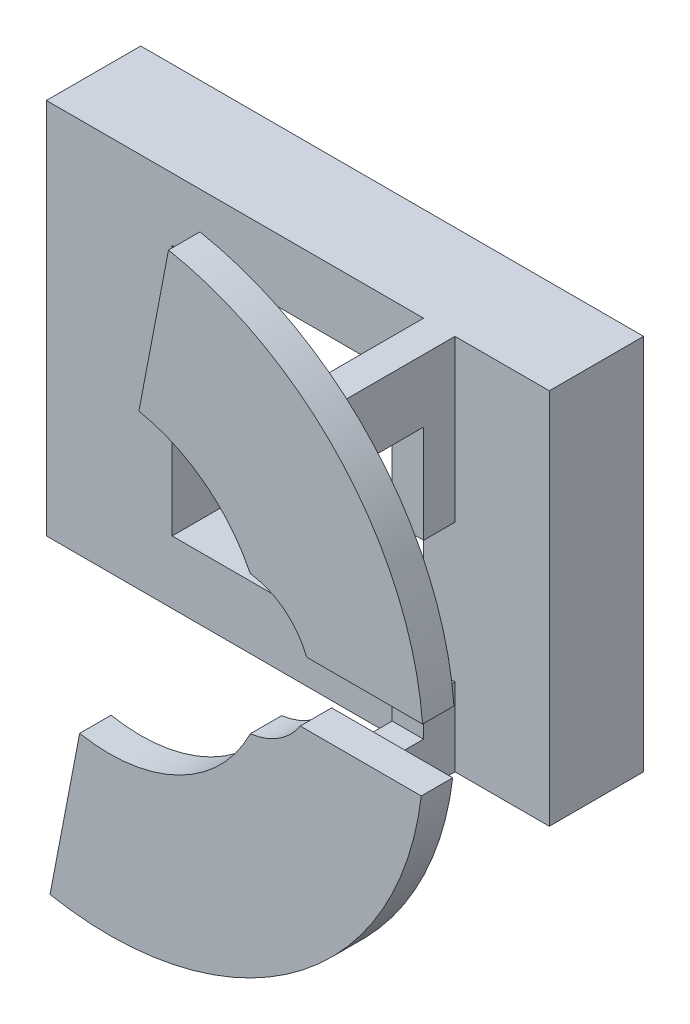
SolidWorks part; units mm, degrees
ref_plane "Front Plane" through (0, 0, 0) normal (1, 0, 0) x (0, 1, 0)
ref_plane "Top Plane" through (0, 0, 0) normal (0, 0, 1) x (0, 1, 0)
ref_plane "Right Plane" through (0, 0, 0) normal (0, 1, 0) x (-1, 0, 0)
sketch "Sketch2" plane through (0, 0, 0) normal (0, 0, 1) x (0, 1, 0)
  line L1 (-20, 20) -> (20, 20)
  line L2 (-20, 20) -> (-20, -20)
  line L3 (-20, -20) -> (20, -20)
  line L4 (20, 20) -> (20, -20)
  line L5 (-20, 20) -> (20, -20) construction
  line L6 (-20, -20) -> (20, 20) construction
  line L11 (-30, -40) -> (30, -40)
  line L12 (-30, -40) -> (-30, 40)
  line L13 (-30, 40) -> (30, 40)
  line L14 (30, -40) -> (30, 40)
  line L15 (-30, -40) -> (30, 40) construction
  line L16 (-30, 40) -> (30, -40) construction
  point P0 (0, 0)
  point P6 (0, 0)
  dimension "D1" = 40
  dimension "D2" = 80
  dimension "D3" = 60
extrude "Boss-Extrude1" add sketch "Sketch2" along normal blind 15
sketch "Sketch6" plane through (0, 0, 15) normal (0, 0, 1) x (1, 0, 0)
  line L0 (40, 30) -> (-40, 30) construction
  line L1 (25, 30) -> (20, 30)
  line L2 (25, 30) -> (25, 4.4)
  line L3 (25, 4.4) -> (20, 4.4)
  line L4 (20, 30) -> (20, 4.4)
  line L5 (20, -20) -> (20, 20) construction
  line L6 (-40, -30) -> (40, -30) construction
  line L7 (25, -30) -> (20, -30)
  line L8 (25, -30) -> (25, -17.6)
  line L9 (25, -17.6) -> (20, -17.6)
  line L10 (20, -30) -> (20, -17.6)
  dimension "D1" = 5
  dimension "D2" = 25.6
  dimension "D3" = 12.4
extrude "Boss-Extrude4" add sketch "Sketch6" along normal blind 5
sketch "Sketch8" plane through (0, 0, 20) normal (0, 0, 1) x (1, 0, 0)
  line L0 (25, -30) -> (25, -17.6) construction
  line L1 (20, -30) -> (25, -30)
  line L2 (20, -30) -> (20, -23)
  line L3 (20, -23) -> (25, -23)
  line L4 (25, -30) -> (25, -23)
  dimension "D1" = 7
extrude "Boss-Extrude5" add sketch "Sketch8" along normal blind 20
sketch "Sketch9" plane through (0, 0, 20) normal (0, 0, 1) x (1, 0, 0)
  line L0 (25, 4.4) -> (25, 30) construction
  line L1 (20, 30) -> (25, 30)
  line L2 (20, 30) -> (20, 20)
  line L3 (20, 20) -> (25, 20)
  line L4 (25, 30) -> (25, 20)
  dimension "D1" = 10
extrude "Boss-Extrude6" add sketch "Sketch9" along normal blind 20
sketch "Sketch10" plane through (0, 0, 40) normal (0, 0, 1) x (1, 0, 0)
  line L0 (0, -42) -> (0, -25) construction
  line L1 (0, 0) -> (42, 0) construction
  line L2 (-9.4249, -49.1037) -> (-4.7124, -24.5518)
  line L3 (4.7124, 24.5518) -> (9.4249, 49.1037)
  line L5 (49.6387, -6) -> (30.375, -6)
  line L7 (49.8397, 4) -> (31.387, 4)
  arc A0 (-9.4249, -49.1037) -> (49.6387, -6) centre (0, 0) ccw
  arc A1 (-4.7124, -24.5518) -> (22.4312, -11.0382) centre (0, 0) ccw
  arc A2 (49.8397, 4) -> (9.4249, 49.1037) centre (0, 0) ccw
  arc A3 (22.4312, 11.0382) -> (4.7124, 24.5518) centre (0, 0) ccw
  arc A4 (22.4312, -11.0382) -> (30.375, -6) centre (21, 0) ccw
  arc A5 (31.387, 4) -> (22.4312, 11.0382) centre (21, 0) ccw
  point P9 (0, 0)
  dimension "D1" = 100
  dimension "D4" = 50
  dimension "D2" = 42
  dimension "D3" = 42
  dimension "D5" = 10
extrude "Boss-Extrude7" add sketch "Sketch10" along normal blind 5
